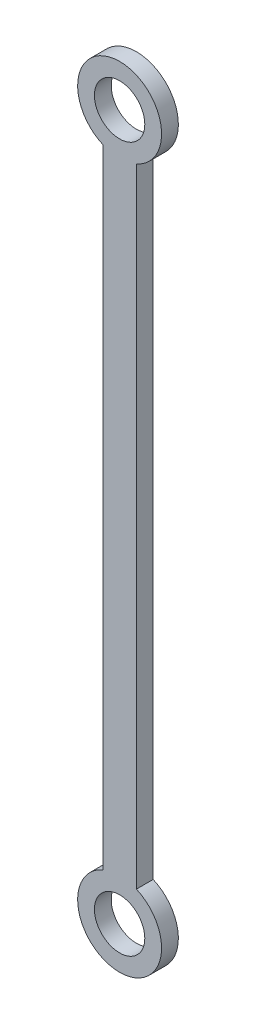
SolidWorks part; units mm, degrees
ref_plane "Plan de face" through (0, 0, 0) normal (0, 0, 1) x (1, 0, 0)
ref_plane "Plan de dessus" through (0, 0, 0) normal (0, 1, 0) x (1, 0, 0)
ref_plane "Plan de droite" through (0, 0, 0) normal (1, 0, 0) x (0, 0, -1)
sketch "Esquisse1" plane through (0, 0, 0) normal (0, 0, 1) x (1, 0, 0)
  line L0 (0, 420) -> (0, 0) construction
  line L1 (-10, 397.0871) -> (-10, 22.9129)
  line L2 (0, 420) -> (0, 165) construction
  line L3 (0, 0) -> (0, -25) construction
  line L4 (10, 397.0871) -> (10, 22.9129)
  circle A0 centre (0, 0) radius 15
  circle A1 centre (0, 420) radius 15
  arc A2 (-10, 397.0871) -> (10, 397.0871) centre (0, 420) cw
  arc A3 (-10, 22.9129) -> (10, 22.9129) centre (0, 0) ccw
  dimension "D2" = 30
  dimension "D3" = 30
  dimension "D4" = 10
  dimension "D5" = 10
  dimension "D1" = 420
  dimension "D6" = 10
extrude "Boss.-Extru.1" add sketch "Esquisse1" along normal blind 10
